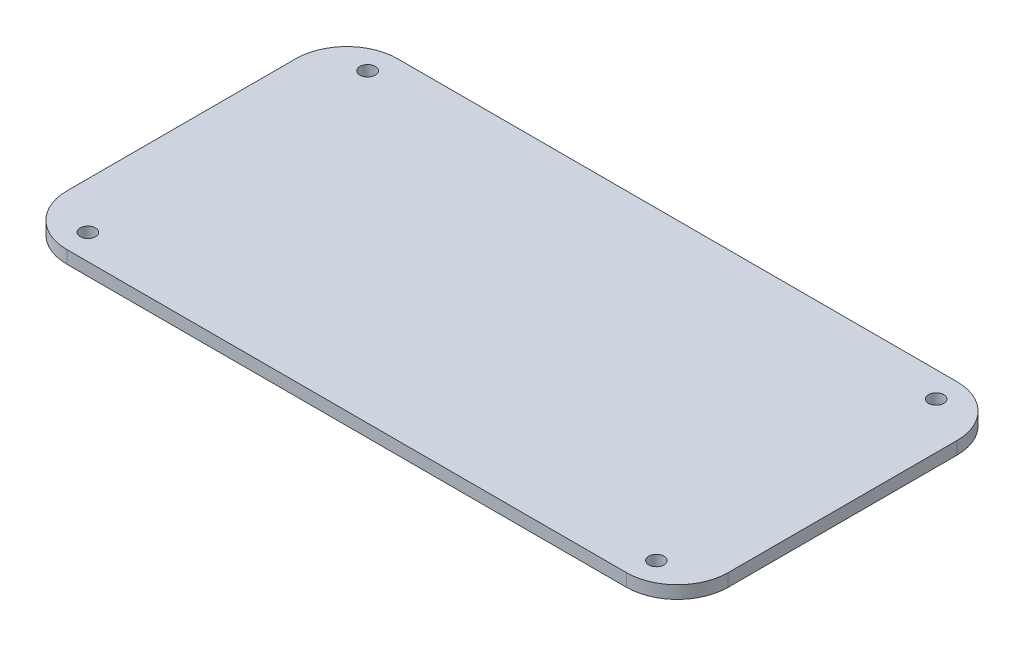
SolidWorks part; units mm, degrees
ref_plane "Front Plane" through (0, 0, 0) normal (0, 0, 1) x (1, 0, 0)
ref_plane "Top Plane" through (0, 0, 0) normal (0, 1, 0) x (1, 0, 0)
ref_plane "Right Plane" through (0, 0, 0) normal (1, 0, 0) x (0, 0, -1)
sketch "Sketch1" plane through (0, 0, 0) normal (0, 1, 0) x (1, 0, 0)
  line L1 (10, 0) -> (120, 0)
  line L2 (0, 10) -> (0, 55)
  line L3 (10, 65) -> (120, 65)
  line L4 (130, 10) -> (130, 55)
  arc A0 (10, 65) -> (0, 55) centre (10, 55) ccw
  arc A1 (0, 10) -> (10, 0) centre (10, 10) ccw
  arc A2 (130, 10) -> (120, 0) centre (120, 10) cw
  arc A3 (120, 65) -> (130, 55) centre (120, 55) cw
  point P7 (0, 65)
  point P10 (0, 0)
  point P13 (130, 0)
  dimension "D3" = 10
  dimension "D4" = 10
  dimension "D5" = 10
  dimension "D6" = 10
  dimension "D1" = 130
  dimension "D2" = 65
extrude "Boss-Extrude1" add sketch "Sketch1" along normal blind 2.5
sketch "Sketch2" plane through (0, 2.5, 0) normal (0, 1, 0) x (1, 0, 0)
  line L0 (0, 55) -> (0, 10) construction
  line L1 (10, 0) -> (120, 0) construction
  line L2 (120, 65) -> (10, 65) construction
  line L3 (65, 55) -> (65, 0) construction
  line L4 (130, 10) -> (130, 55) construction
  circle A0 centre (9.1127, 5) radius 1.5
  circle A1 centre (9.1127, 60) radius 1.5
  circle A2 centre (120.8873, 5) radius 1.5
  circle A3 centre (120.8873, 60) radius 1.5
  point P16 (0, 0)
  point P17 (0, 0)
  dimension "D1" = 3
  dimension "D4" = 3
  dimension "D2" = 9.1127
  dimension "D3" = 5
  dimension "D5" = 5
  dimension "D6" = 9.1127
extrude "Cut-Extrude1" cut sketch "Sketch2" against normal through all
sketch "Sketch7" plane through (0, 2.5, 0) normal (0, 1, 0) x (1, 0, 0)
